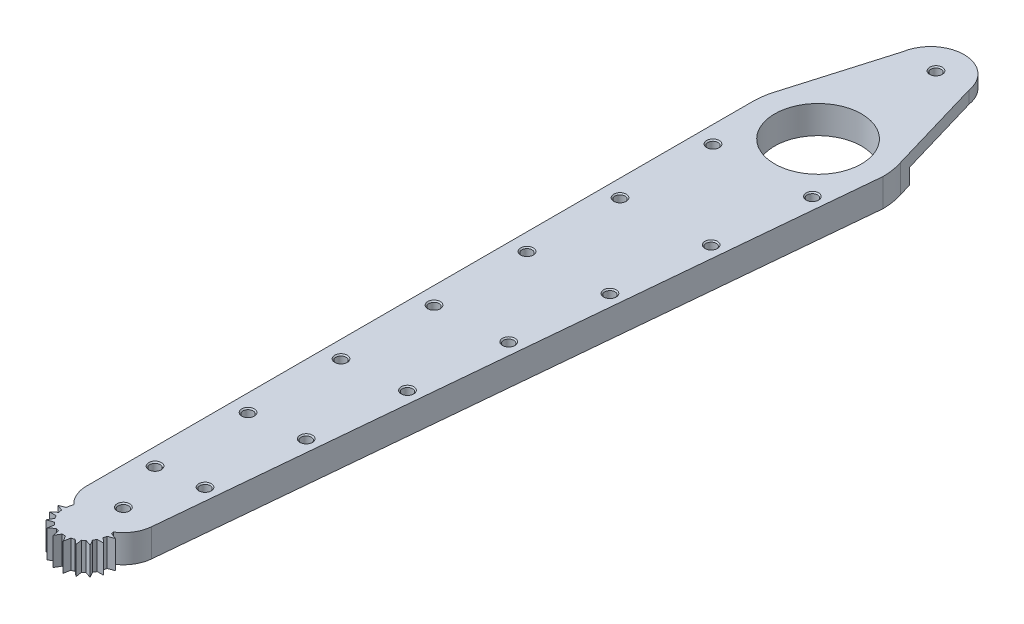
SolidWorks part; units mm, degrees
ref_plane "前视基准面" through (0, 0, 0) normal (0, 0, 1) x (1, 0, 0)
ref_plane "上视基准面" through (0, 0, 0) normal (0, 1, 0) x (1, 0, 0)
ref_plane "右视基准面" through (0, 0, 0) normal (1, 0, 0) x (0, 0, -1)
sketch "草图1" plane through (0, 0, 0) normal (0, 1, 0) x (1, 0, 0)
  line L0 (-21, 0) -> (-21, -215)
  line L1 (21, 0) -> (0.8466, -215.9293)
  line L2 (-11, -225) -> (-9.1101, -225)
  arc A0 (21, 0) -> (-21, 0) centre (0, 0) ccw
  arc A1 (-21, -215) -> (-11, -225) centre (-11, -215) ccw
  arc A2 (0.8466, -215.9293) -> (-9.1101, -225) centre (-9.1101, -215) cw
  dimension "D1" = 10
extrude "凸台-拉伸1" add sketch "草图1" along normal blind 15 contours L0 A1 L2 A2 L1 A0
sketch "草图2" plane through (0, 0, 0) normal (0, -1, 0) x (1, 0, 0)
  line L0 (0, 24.8705) -> (-8.6819, 198.279) construction
  line L1 (-6.4875, 24.5457) -> (-15.1695, 197.9542)
  line L2 (6.4875, 25.1953) -> (-2.1944, 198.6038)
  arc A0 (-6.4875, 24.5457) -> (6.4875, 25.1953) centre (0, 24.8705) ccw
  arc A1 (-2.1944, 198.6038) -> (-15.1695, 197.9542) centre (-8.6819, 198.279) ccw
  point P2 (-4.341, 111.5747)
extrude "切除-拉伸1" cut sketch "草图2" against normal blind 4
sketch "草图3" plane through (0, 0, 0) normal (0, -1, 0) x (-1, 0, 0)
  circle A0 centre (0, 0) radius 14
extrude "切除-拉伸2" cut sketch "草图3" against normal through all
sketch "草图7" plane through (0, 0, 0) normal (0, 1, 0) x (1, 0, 0)
  line L0 (-20.3523, 5.1751) -> (-10.6931, 38.0391)
  line L1 (20.3523, 5.1751) -> (10.6931, 38.0391)
  arc A0 (21, 0) -> (-21, 0) centre (0, 0) ccw construction
  arc A1 (10.6931, 38.0391) -> (-10.6931, 38.0391) centre (0, 36.2761) ccw
  arc A2 (20.3523, 5.1751) -> (-20.3523, 5.1751) centre (0, 0) ccw
extrude "凸台-拉伸4" add sketch "草图7" along normal blind 15 contours A2 L1 A1 L0
sketch "草图11" plane through (0, 0, 0) normal (1, 0, 0) x (0, 0, -1)
  line L12 (47.1135, 15) -> (38.0391, 15) construction
  line L13 (43.0391, 12.5) -> (60.0391, 12.5)
  line L14 (43.0391, 12.5) -> (43.0391, 2.5)
  line L15 (43.0391, 2.5) -> (60.0391, 2.5)
  line L16 (60.0391, 12.5) -> (60.0391, 2.5)
  line L17 (38.0391, 0) -> (47.1135, 0) construction
  line L18 (38.0391, 15) -> (38.0391, 0) construction
  dimension "D1" = 2.5
  dimension "D2" = 2.5
  dimension "D3" = 5
  dimension "D4" = 17
sketch "草图12" plane through (0, 0, 0) normal (1, 0, 0) x (0, 0, -1)
  line L0 (38.0391, 15) -> (38.0391, 0)
revolve "切除-旋转3" cut sketch "草图11" angle 360 about L0
sketch "草图14" plane through (0, 0, 0) normal (1, 0, 0) x (0, 0, -1)
  line L2 (22.2603, 12.5) -> (16.2603, 12.5)
  line L3 (22.2603, 12.5) -> (22.2603, 2.5)
  line L4 (22.2603, 2.5) -> (16.2603, 2.5)
  line L5 (16.2603, 12.5) -> (16.2603, 2.5)
  dimension "D1" = 6
sketch "草图15" plane through (0, 0, 0) normal (1, 0, 0) x (0, 0, -1)
  line L0 (0, 15) -> (0, 0)
revolve "切除-旋转4" cut sketch "草图14" angle 60 about L0 other way angle 90
sketch "草图16" plane through (20.1341, 0, -5.9177) normal (0.9594, 0, -0.282) x (-0.282, 0, -0.9594)
  line L0 (17.0339, 12.5) -> (17.0339, 2.5) construction
  line L1 (7.4244, 12.5) -> (17.0339, 12.5)
  line L2 (7.4244, 12.5) -> (7.4244, 2.5)
  line L3 (7.4244, 2.5) -> (17.0339, 2.5)
  line L4 (17.0339, 12.5) -> (17.0339, 2.5)
extrude "切除-拉伸4" cut sketch "草图16" against normal blind 5
sketch "草图17" plane through (-20.1341, 0, -5.9177) normal (-0.9594, 0, -0.282) x (-0.282, 0, 0.9594)
  line L1 (-17.0339, 12.5) -> (-7.4244, 12.5)
  line L2 (-17.0339, 12.5) -> (-17.0339, 2.5)
  line L3 (-17.0339, 2.5) -> (-7.4244, 2.5)
  line L4 (-7.4244, 12.5) -> (-7.4244, 2.5)
extrude "切除-拉伸5" cut sketch "草图17" against normal blind 5
sketch "草图20" plane through (0, 0, 0) normal (0, -1, 0) x (1, 0, 0)
  line L5 (21, 0) -> (0.8466, 215.9293)
  line L6 (-9.1101, 225) -> (-11, 225)
  line L7 (-21, 215) -> (-21, 0)
  line L8 (-19.9158, -6.6604) -> (-10.6931, -38.0391)
  line L9 (10.6931, -38.0391) -> (19.9158, -6.6604)
  line L10 (21, 0) -> (0.8466, 215.9293)
  line L11 (-9.1101, 225) -> (-11, 225)
  line L12 (-21, 215) -> (-21, 0)
  line L13 (-19.9158, -6.6604) -> (-10.6931, -38.0391)
  line L14 (10.6931, -38.0391) -> (19.9158, -6.6604)
  arc A5 (19.9158, -6.6604) -> (21, 0) centre (0, 0) ccw
  arc A6 (0.8466, 215.9293) -> (-9.1101, 225) centre (-9.1101, 215) ccw
  arc A7 (-11, 225) -> (-21, 215) centre (-11, 215) ccw
  arc A8 (-21, 0) -> (-19.9158, -6.6604) centre (0, 0) ccw
  arc A9 (-10.6931, -38.0391) -> (10.6931, -38.0391) centre (0, -36.2761) ccw
  arc A10 (19.9158, -6.6604) -> (21, 0) centre (0, 0) ccw
  arc A11 (0.8466, 215.9293) -> (-9.1101, 225) centre (-9.1101, 215) ccw
  arc A12 (-11, 225) -> (-21, 215) centre (-11, 215) ccw
  arc A13 (-21, 0) -> (-19.9158, -6.6604) centre (0, 0) ccw
  arc A14 (-10.6931, -38.0391) -> (10.6931, -38.0391) centre (0, -36.2761) ccw
  dimension "D1" = 0
extrude "切除-拉伸6" cut sketch "草图20" against normal blind 7.5
sketch "草图21" plane through (0, 7.5, 0) normal (0, -1, 0) x (1, 0, 0)
  line L6 (-21, 0) -> (-16.2603, 0)
  line L7 (14.0819, -8.1302) -> (18.7001, -10.7965)
  line L8 (18.7001, -10.7965) -> (19.9158, -6.6604)
  line L9 (21, 0) -> (0.8466, 215.9293)
  line L10 (-9.1101, 225) -> (-11, 225)
  line L11 (-21, 215) -> (-21, 0)
  line L12 (-21, 0) -> (-16.2603, 0)
  line L13 (14.0819, -8.1302) -> (18.7001, -10.7965)
  line L14 (18.7001, -10.7965) -> (19.9158, -6.6604)
  line L15 (21, 0) -> (0.8466, 215.9293)
  line L16 (-9.1101, 225) -> (-11, 225)
  line L17 (-21, 215) -> (-21, 0)
  circle A0 centre (0, 0) radius 14 construction
  circle A1 centre (0, -38.0391) radius 5
  circle A2 centre (0, -38.0391) radius 5
  circle A3 centre (0, 0) radius 14
  arc A6 (-16.2603, 0) -> (-2.0308, -16.133) centre (0, 0) ccw
  arc A7 (2.0308, -16.133) -> (-2.0308, -16.133) centre (0, -38.0391) ccw
  arc A8 (2.0308, -16.133) -> (14.0819, -8.1302) centre (0, 0) ccw
  arc A9 (19.9158, -6.6604) -> (21, 0) centre (0, 0) ccw
  arc A10 (0.8466, 215.9293) -> (-9.1101, 225) centre (-9.1101, 215) ccw
  arc A11 (-11, 225) -> (-21, 215) centre (-11, 215) ccw
  arc A12 (-16.2603, 0) -> (-2.0308, -16.133) centre (0, 0) ccw
  arc A13 (2.0308, -16.133) -> (-2.0308, -16.133) centre (0, -38.0391) ccw
  arc A14 (2.0308, -16.133) -> (14.0819, -8.1302) centre (0, 0) ccw
  arc A15 (19.9158, -6.6604) -> (21, 0) centre (0, 0) ccw
  arc A16 (0.8466, 215.9293) -> (-9.1101, 225) centre (-9.1101, 215) ccw
  arc A17 (-11, 225) -> (-21, 215) centre (-11, 215) ccw
  dimension "D1" = 0
  dimension "D2" = 0
sketch "草图22" plane through (0, 12.5, 0) normal (0, -1, 0) x (1, 0, 0)
  line L4 (-19.9158, -6.6604) -> (-10.6931, -38.0391)
  line L5 (10.6931, -38.0391) -> (18.7001, -10.7965)
  line L6 (18.7001, -10.7965) -> (14.0819, -8.1302)
  line L7 (-16.2603, 0) -> (-21, 0)
  line L8 (-19.9158, -6.6604) -> (-10.6931, -38.0391)
  line L9 (10.6931, -38.0391) -> (18.7001, -10.7965)
  line L10 (18.7001, -10.7965) -> (14.0819, -8.1302)
  line L11 (-16.2603, 0) -> (-21, 0)
  arc A5 (-21, 0) -> (-19.9158, -6.6604) centre (0, 0) ccw
  arc A6 (-10.6931, -38.0391) -> (10.6931, -38.0391) centre (0, -36.2761) ccw
  arc A7 (2.0308, -16.133) -> (14.0819, -8.1302) centre (0, 0) ccw
  arc A8 (2.0308, -16.133) -> (-2.0308, -16.133) centre (0, -38.0391) ccw
  arc A9 (-16.2603, 0) -> (-2.0308, -16.133) centre (0, 0) ccw
  arc A10 (-21, 0) -> (-19.9158, -6.6604) centre (0, 0) ccw
  arc A11 (-10.6931, -38.0391) -> (10.6931, -38.0391) centre (0, -36.2761) ccw
  arc A12 (2.0308, -16.133) -> (14.0819, -8.1302) centre (0, 0) ccw
  arc A13 (2.0308, -16.133) -> (-2.0308, -16.133) centre (0, -38.0391) ccw
  arc A14 (-16.2603, 0) -> (-2.0308, -16.133) centre (0, 0) ccw
  dimension "D1" = 0
extrude "凸台-拉伸6" add sketch "草图22" along normal blind 1.5
extrude "凸台-拉伸7" add sketch "草图21" along normal blind 1.5
sketch "草图23" plane through (0, 15, 0) normal (0, 1, 0) x (1, 0, 0)
  point P0 (-4.3384, -226.0968) [skipped]
  point P2 (-9.1101, -215)
  point P3 (15.1767, -17.0055)
  point P4 (0, 38.0391)
  point P8 (-15.5, -18.3981)
  point P9 (-15.5, -48.3981)
  point P10 (-15.5, -78.3981)
  point P11 (-15.5, -108.3981)
  point P12 (-15.5, -138.3981)
  point P13 (-15.5, -168.3981)
  point P14 (-15.5, -198.3981)
  point P17 (12.3889, -46.8757)
  point P18 (9.601, -76.7459)
  point P21 (6.8131, -106.616)
  point P22 (4.0252, -136.4862)
  point P23 (1.2373, -166.3564)
  point P24 (-1.5506, -196.2266)
  dimension "D1" = 7
  dimension "D5" = 8
hole_wizard "M4 螺纹孔1" positions "草图23" profile "草图24" tap size "M4" standard "DIN" end condition up to next
sketch "草图24" plane through (-1.5506, 15, 196.2266) normal (1, 0, 0) x (0, 0, 1)
  line L0 (0, 0) -> (0, 9)
  line L1 (0, 9) -> (1.65, 9)
  line L2 (1.65, 9) -> (1.65, 0.375)
  line L3 (1.65, 0.375) -> (2.025, 0)
  line L5 (2.025, 0) -> (0, 0)
  line L6 (-1.65, 0.375) -> (-2.025, 0) construction
  line L11 (0, -6.35) -> (0, 107.95) construction
  dimension "通孔螺纹孔钻头直径" = 3.3
  dimension "通孔螺纹孔钻头深度" = 9
  dimension "近端锥形沉头孔直径" = 4.05
  dimension "近端锥形沉头孔角度" = 90
cosmetic thread "孔螺纹线1" parameters "D2"=4
cosmetic thread "孔螺纹线2" parameters "D2"=4
cosmetic thread "孔螺纹线3" parameters "D2"=4
cosmetic thread "孔螺纹线4" parameters "D2"=4
cosmetic thread "孔螺纹线5" parameters "D2"=4
cosmetic thread "孔螺纹线6" parameters "D2"=4
cosmetic thread "孔螺纹线7" parameters "D2"=4
cosmetic thread "孔螺纹线8" parameters "D2"=4
cosmetic thread "孔螺纹线9" parameters "D2"=4
cosmetic thread "孔螺纹线10" parameters "D2"=4
cosmetic thread "孔螺纹线11" parameters "D2"=4
cosmetic thread "孔螺纹线12" parameters "D2"=4
cosmetic thread "孔螺纹线13" parameters "D2"=4
cosmetic thread "孔螺纹线14" parameters "D2"=4
cosmetic thread "孔螺纹线15" parameters "D2"=4
cosmetic thread "孔螺纹线16" parameters "D2"=4
sketch "草图25" plane through (0, 6, 0) normal (0, -1, 0) x (1, 0, 0)
  circle A1 centre (0, -38.0391) radius 5
  circle A2 centre (0, -38.0391) radius 5
  dimension "D1" = 0
extrude "切除-拉伸7" cut sketch "草图25" against normal blind 5
sketch "草图26" plane through (0, 15, 0) normal (0, 1, 0) x (1, 0, 0)
  line L0 (-18.3078, -224.2664) -> (-20.2841, -225)
  line L1 (-20.2841, -225) -> (-18.3078, -225.7336)
  line L2 (-19.7242, -228.1753) -> (-17.6162, -228.1888)
  line L3 (-18.118, -226.81) -> (-19.7242, -228.1753)
  line L4 (-18.112, -230.9677) -> (-16.1265, -230.2594)
  line L5 (-17.0697, -229.1354) -> (-18.112, -230.9677)
  line L6 (-15.642, -233.0403) -> (-14.0186, -231.6956)
  line L7 (-15.2892, -230.9619) -> (-15.642, -233.0403)
  line L8 (-12.6122, -234.1431) -> (-11.5465, -232.3242)
  line L9 (-12.9915, -232.0694) -> (-12.6122, -234.1431)
  line L10 (-9.3878, -234.1431) -> (-9.0085, -232.0694)
  line L11 (-10.4535, -232.3242) -> (-9.3878, -234.1431)
  line L12 (-6.358, -233.0403) -> (-6.7108, -230.9619)
  line L13 (-7.9814, -231.6956) -> (-6.358, -233.0403)
  line L14 (-3.888, -230.9677) -> (-4.9303, -229.1354)
  line L15 (-5.8735, -230.2594) -> (-3.888, -230.9677)
  line L16 (-2.2758, -228.1753) -> (-3.882, -226.81)
  line L17 (-4.3838, -228.1888) -> (-2.2758, -228.1753)
  line L18 (-1.7159, -225) -> (-3.6922, -224.2664)
  line L19 (-3.6922, -225.7336) -> (-1.7159, -225)
  arc A0 (-18.3078, -225.7336) -> (-18.118, -226.81) centre (-11, -225) ccw
  arc A1 (-17.6162, -228.1888) -> (-17.0697, -229.1354) centre (-11, -225) ccw
  arc A2 (-16.1265, -230.2594) -> (-15.2892, -230.9619) centre (-11, -225) ccw
  arc A3 (-14.0186, -231.6956) -> (-12.9915, -232.0694) centre (-11, -225) ccw
  arc A4 (-11.5465, -232.3242) -> (-10.4535, -232.3242) centre (-11, -225) ccw
  arc A5 (-9.0085, -232.0694) -> (-7.9814, -231.6956) centre (-11, -225) ccw
  arc A6 (-6.7108, -230.9619) -> (-5.8735, -230.2594) centre (-11, -225) ccw
  arc A7 (-4.9303, -229.1354) -> (-4.3838, -228.1888) centre (-11, -225) ccw
  arc A8 (-3.882, -226.81) -> (-3.6922, -225.7336) centre (-11, -225) ccw
  arc A9 (-3.6922, -224.2664) -> (-18.3078, -224.2664) centre (-11, -225) ccw
  point P36 (-11, -225)
  dimension "D1" = 10
extrude "凸台-拉伸8" add sketch "草图26" against normal blind 9 contours L5 L4 A2 L7 L6 A3 L9 L8 A4 L11 L10 A5 L13 L12 A6 L15 L14 A7 L17 L16 A8 L19 L18 A9 L0 L1 A0 L3 L2 A1
